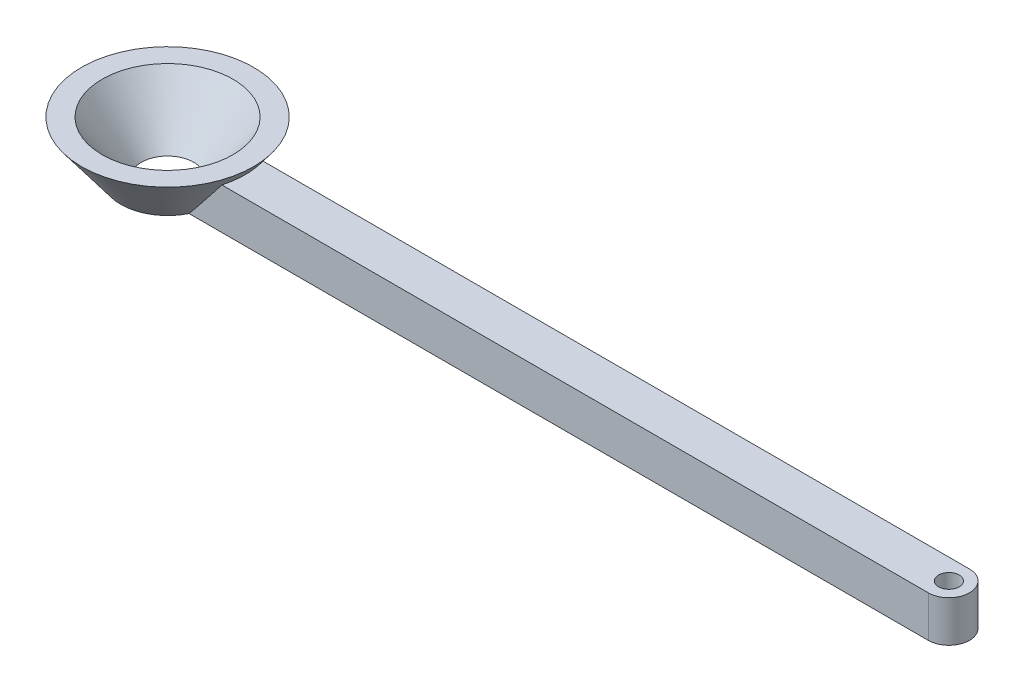
SolidWorks part; units mm, degrees
ref_plane "Front Plane" through (0, 0, 0) normal (0, 0, 1) x (1, 0, 0)
ref_plane "Top Plane" through (0, 0, 0) normal (0, 1, 0) x (1, 0, 0)
ref_plane "Right Plane" through (0, 0, 0) normal (1, 0, 0) x (0, 0, -1)
sketch "Sketch1" plane through (0, 0, 0) normal (0, 1, 0) x (1, 0, 0)
  line L1 (90, -5) -> (-90, -5)
  line L3 (90, 5) -> (-90, 5)
  line L4 (-90, -5) -> (-90, 5)
  line L5 (90, -5) -> (-90, 5) construction
  line L6 (90, 5) -> (-90, -5) construction
  line L7 (2.3241, -0.4022) -> (2.3241, -0.4064)
  arc A0 (90, 5) -> (90, -5) centre (90, 0) cw
  circle A1 centre (90, 0) radius 2.5
  point P0 (0, 0)
  dimension "D1" = 10
  dimension "D2" = 180
extrude "Boss-Extrude2" add sketch "Sketch1" along normal blind 10 contours A0 L3 L4 L1 A1
sketch "Sketch6" plane through (0, 0, 0) normal (0, 0, 1) x (1, 0, 0)
  line L0 (-99.525, 14.8262) -> (-99.525, -3.9847) construction
  line L1 (-90, 10) -> (-90, 0) construction
  line L2 (-88.175, 0) -> (-78.65, 12.7)
  line L3 (-93.175, 0) -> (-88.175, 0)
  line L4 (-78.65, 12.7) -> (-83.65, 12.7)
  line L5 (-83.65, 12.7) -> (-93.175, 0)
  line L6 (90, 0) -> (-90, 0) construction
  dimension "D1" = 9.525
  dimension "D2" = 6.35
  dimension "D3" = 15.875
  dimension "D4" = 5
  dimension "D5" = 12.7
revolve "Revolve2" add sketch "Sketch6" angle 360 about L0
sketch "Sketch7" plane through (0, 0, 0) normal (0, 0, 1) x (1, 0, 0)
  line L0 (-99.525, 12.7) -> (-99.525, 0) construction
  line L3 (-78.65, 12.7) -> (-120.4, 12.7) construction
  line L4 (-110.875, 0) -> (-89.3357, 0) construction
  line L5 (-83.65, 12.7) -> (-93.175, 0)
  line L6 (-93.175, 0) -> (-99.525, 0)
  line L7 (-99.525, 0) -> (-99.525, 12.7)
  line L8 (-99.525, 12.7) -> (-83.65, 12.7)
revolve "Cut-Revolve1" cut sketch "Sketch7" angle 360 about L0
